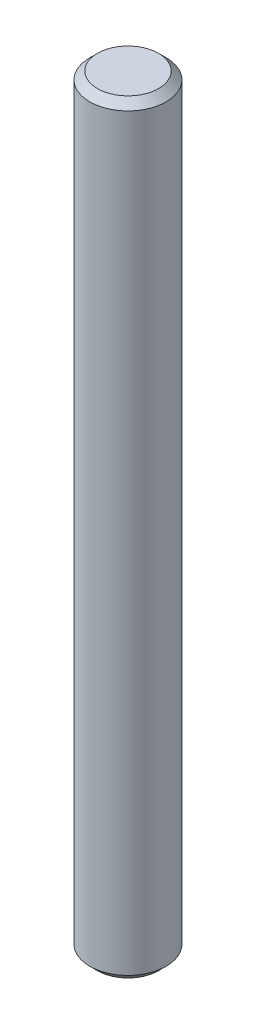
SolidWorks part; units mm, degrees
material "AISI 304"
ref_plane "Front Plane" through (0, 0, 0) normal (0, 0, 1) x (1, 0, 0)
ref_plane "Top Plane" through (0, 0, 0) normal (0, 1, 0) x (1, 0, 0)
ref_plane "Right Plane" through (0, 0, 0) normal (1, 0, 0) x (0, 0, -1)
sketch "Sketch1" plane through (0, 0, 0) normal (0, 1, 0) x (1, 0, 0)
  circle A0 centre (0, 0) radius 1
  dimension "D1" = 2
extrude "Boss-Extrude1" add sketch "Sketch1" along normal blind 20
chamfer "Chamfer1" distance 0.2 angle 45 2 edges at (0, 0, 1) (0, 20, 1)
